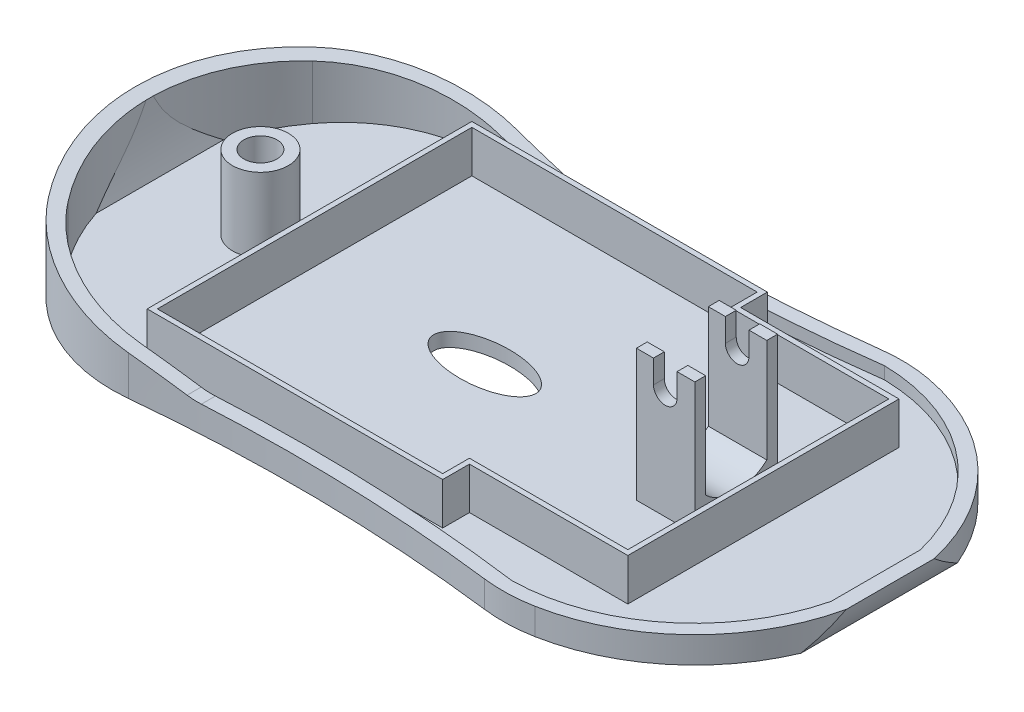
SolidWorks part; units mm, degrees
material "PVC 0.007 Plasticized"
ref_plane "Front Plane" through (0, 0, 0) normal (0, 0, 1) x (1, 0, 0)
ref_plane "Top Plane" through (0, 0, 0) normal (0, 1, 0) x (1, 0, 0)
ref_plane "Right Plane" through (0, 0, 0) normal (1, 0, 0) x (0, 0, -1)
sketch "Sketch1" plane through (0, 0, 0) normal (0, 0, 1) x (1, 0, 0)
  line L1 (0, 0) -> (119.3, 0)
  line L2 (0, 0) -> (0, 12.57)
  line L3 (0, 12.57) -> (119.3, 12.57)
  line L4 (119.3, 0) -> (119.3, 12.57)
  dimension "D1" = 119.3
  dimension "D2" = 12.57
extrude "Boss-Extrude1" add sketch "Sketch1" against normal blind 62.92
sketch "Sketch2" plane through (0, 0, 0) normal (0, 0, 1) x (1, 0, 0)
  line L1 (0, 0) -> (119.3, 0) construction
  line L2 (2.5, 0) -> (0, 0)
  line L3 (0, 0) -> (0, 12.57)
  line L5 (116.8, 0) -> (119.3, 0)
  line L6 (119.3, 0) -> (119.3, 12.57) construction
  line L7 (119.3, 0) -> (119.3, 12.57)
  spline S0 degree 3 poles (119.3, 12.57) (119.2765, 8.0883) (119.1768, 3.9203) (116.8, 0) knots 0 0 0 0 1 1 1 1
  spline S1 degree 3 poles (0, 12.57) (0.0438, 8.0816) (0.109, 3.9225) (2.5, 0) knots 0 0 0 0 1 1 1 1
  dimension "D1" = 2.5
  dimension "D2" = 2.5
extrude "Cut-Extrude1" cut sketch "Sketch2" against normal through all
sketch "Sketch3" plane through (0, 12.57, 0) normal (0, 1, 0) x (1, 0, 0)
  line L0 (119.3, 62.92) -> (0, 62.92) construction
  line L1 (119.3, 0) -> (0, 0) construction
  line L2 (0, 62.92) -> (0, 0) construction
  line L4 (37.6405, 60.68) -> (78.8534, 60.68) construction
  line L5 (119.3, 62.92) -> (119.3, 0) construction
  arc A0 (20.6, 62.92) -> (20.6, 0) centre (34.3226, 31.46) ccw
  arc A1 (88.28, 62.92) -> (88.28, 0) centre (87.8369, 31.46) cw
  arc A2 (20.6, 62.92) -> (88.28, 62.92) centre (54.44, 317.4129) ccw
  arc A3 (20.6, 0) -> (88.28, 0) centre (54.44, -254.4929) cw
  dimension "D3" = 29.22
  dimension "D1" = 20.6
  dimension "D2" = 31.02
extrude "Cut-Extrude2" cut sketch "Sketch3" against normal through all flip side to cut
ref_plane "Plane1" through (0, 0, 25.65) normal (0, 0, 1) x (1, 0, 0)
sketch "Sketch4" plane through (0, 0, 25.65) normal (0, 0, 1) x (1, 0, 0)
  line L0 (0, 12.57) -> (37.8415, 4.367)
  line L1 (39.96, 4.14) -> (135.606, 4.14)
  line L2 (0, 12.57) -> (135.606, 12.57)
  line L3 (135.606, 12.57) -> (135.606, 4.14)
  line L4 (20.6, 0) -> (88.28, 0) construction
  line L5 (2.5, 0) -> (20.6, 0) construction
  arc A0 (37.8415, 4.367) -> (39.96, 4.14) centre (39.96, 14.14) ccw
  dimension "D1" = 10
  dimension "D2" = 39.96
  dimension "D3" = 4.14
extrude "Cut-Extrude3" cut sketch "Sketch4" against normal through all
fillet "Fillet2" radius 25 2 edges at (20.6, 4.0522, -62.92) (20.6, 4.0522, 0)
shell "Shell1" thickness 2.2
sketch "Sketch5" plane through (0, 2.2, 0) normal (0, 1, 0) x (1, 0, 0)
  line L0 (17.7564, 62.0342) -> (40.8167, 62.0342) construction
  line L1 (-6.1271, 31.46) -> (147.6828, 31.46) construction
  line L3 (3.8023, 41.4786) -> (3.8023, 21.4414) construction
  line L9 (77.7725, 62.9231) -> (104.4387, 62.9231) construction
  circle A0 centre (19.605, 31.46) radius 2.61
  circle A1 centre (19.605, 31.46) radius 4.4
  arc A3 (29.2983, 61.914) -> (6.8112, 51.9822) centre (26.85, 37.0342) ccw construction
  arc A4 (118.535, 38.3558) -> (88.28, 62.92) centre (87.8369, 31.46) ccw construction
  point P15 (3.8023, 31.46)
  dimension "D2" = 5.22
  dimension "D3" = 8.8
  dimension "D1" = 17.4
fillet "Fillet3" radius 25 2 edges at (88.28, 2.07, -62.92) (88.28, 2.07, 0)
extrude "Boss-Extrude2" add sketch "Sketch5" along normal blind 11.6
sketch "Sketch6" plane through (0, 2.2, 0) normal (0, 1, 0) x (1, 0, 0)
  line L0 (81.167, 62.8117) -> (101.4323, 62.8117) construction
  line L1 (85.255, 37.8717) -> (94.435, 37.8717)
  line L2 (85.255, 37.8717) -> (85.255, 24.8717)
  line L3 (85.255, 24.8717) -> (94.435, 24.8717)
  line L4 (94.435, 37.8717) -> (94.435, 24.8717)
  line L5 (118.535, 38.3558) -> (118.535, 24.5642) construction
  arc A0 (93.654, 62.3807) -> (85.9623, 62.6225) centre (89.0318, 37.8117) ccw construction
  dimension "D1" = 13
  dimension "D2" = 9.18
  dimension "D3" = 24.94
  dimension "D4" = 24.1
extrude "Boss-Extrude3" add sketch "Sketch6" along normal blind 20.68
sketch "Sketch7" plane through (0, 0, -24.8717) normal (0, 0, 1) x (1, 0, 0)
  line L0 (85.255, 22.88) -> (94.435, 22.88) construction
  line L1 (87.935, 22.88) -> (91.635, 22.88)
  line L2 (87.935, 22.88) -> (87.935, 19.23)
  line L4 (91.635, 22.88) -> (91.635, 19.23)
  line L5 (85.255, 22.88) -> (85.255, 2.2) construction
  arc A0 (87.935, 19.23) -> (91.635, 19.23) centre (89.785, 19.23) ccw
  dimension "D4" = 3.7
  dimension "D1" = 3.65
  dimension "D2" = 3.7
  dimension "D3" = 2.68
extrude "Cut-Extrude4" cut sketch "Sketch7" against normal up to surface (13 mm away) up to face at (89.845, 12.54, -37.8717)
sketch "Sketch8" plane through (94.435, 0, 0) normal (1, 0, 0) x (0, 0, -1)
  line L0 (24.8717, 22.88) -> (37.8717, 22.88) construction
  line L1 (26.5717, 22.88) -> (36.1717, 22.88)
  line L2 (26.5717, 22.88) -> (26.5717, 6.6178)
  line L4 (36.1717, 22.88) -> (36.1717, 6.6178)
  line L5 (24.8717, 22.88) -> (24.8717, 2.2) construction
  line L6 (37.8717, 22.88) -> (37.8717, 2.2) construction
  arc A0 (26.5717, 6.6178) -> (36.1717, 6.6178) centre (31.3717, 11.6843) ccw
  dimension "D3" = 6.9793
  dimension "D5" = 4.8
  dimension "D1" = 1.7
  dimension "D2" = 1.7
  dimension "D4" = 11.1957
extrude "Cut-Extrude5" cut sketch "Sketch8" against normal up to surface (9.18 mm away) up to face at (85.255, 12.54, -31.3717)
sketch "Sketch9" plane through (0, 2.2, 0) normal (0, 1, 0) x (1, 0, 0)
  line L0 (29.7996, 58.48) -> (88.7664, 58.48) construction
  line L4 (116.2498, 38.4626) -> (116.2498, 24.4574) construction
  arc A1 (39.96, 58.8852) -> (88.4069, 60.7176) centre (54.44, 317.4129) ccw construction
  ellipse E0 centre (54.8298, 31.48) end of major axis (62.8448, 31.48) minor radius 3.9
  dimension "D1" = 27
  dimension "D2" = 61.42
  dimension "D3" = 7.8
  dimension "D4" = 16.03
  dimension "D5" = 23.1
extrude "Cut-Extrude6" cut sketch "Sketch9" against normal up to surface (2.2 mm away) up to face at (55.9735, 0, -31.46)
sketch "Sketch10" plane through (0, 2.2, 0) normal (0, 1, 0) x (1, 0, 0)
  line L8 (116.2498, 38.4626) -> (116.2498, 24.4574) construction
  line L9 (24.0048, 31.5008) -> (24.0048, 47.615) construction
  line L10 (94.435, 37.8717) -> (85.255, 37.8717) construction
  line L23 (73.8248, 56.8717) -> (73.8248, 52.6717)
  line L24 (27.4048, 56.8717) -> (73.8248, 56.8717)
  line L25 (27.4048, 5.8717) -> (27.4048, 56.8717)
  line L26 (73.8248, 10.0717) -> (73.8248, 5.8717)
  line L27 (73.8248, 5.8717) -> (27.4048, 5.8717)
  line L28 (98.7048, 10.0717) -> (73.8248, 10.0717)
  line L37 (98.7048, 52.6717) -> (73.8248, 52.6717)
  line L38 (98.7048, 52.6717) -> (98.7048, 10.0717)
  line L39 (85.255, 24.8717) -> (94.435, 24.8717) construction
  line L41 (28.2048, 56.0717) -> (73.0248, 56.0717)
  line L42 (73.0248, 56.0717) -> (73.0248, 51.8717)
  line L43 (97.9048, 51.8717) -> (73.0248, 51.8717)
  line L44 (97.9048, 51.8717) -> (97.9048, 10.8717)
  line L45 (97.9048, 10.8717) -> (73.0248, 10.8717)
  line L46 (73.0248, 10.8717) -> (73.0248, 6.6717)
  line L47 (73.0248, 6.6717) -> (28.2048, 6.6717)
  line L48 (28.2048, 6.6717) -> (28.2048, 56.0717)
  circle A1 centre (19.605, 31.46) radius 4.4 construction
  circle A2 centre (19.605, 31.46) radius 4.4 construction
  dimension "D1" = 3.4
  dimension "D2" = 71.3
  dimension "D3" = 24.88
  dimension "D4" = 17.545
  dimension "D5" = 14.8
  dimension "D6" = 4.2
  dimension "D7" = 14.8
  dimension "D8" = 24.88
  dimension "D9" = 4.2
  dimension "D10" = 0.8
extrude "Boss-Extrude4" add sketch "Sketch10" along normal blind 6.6
